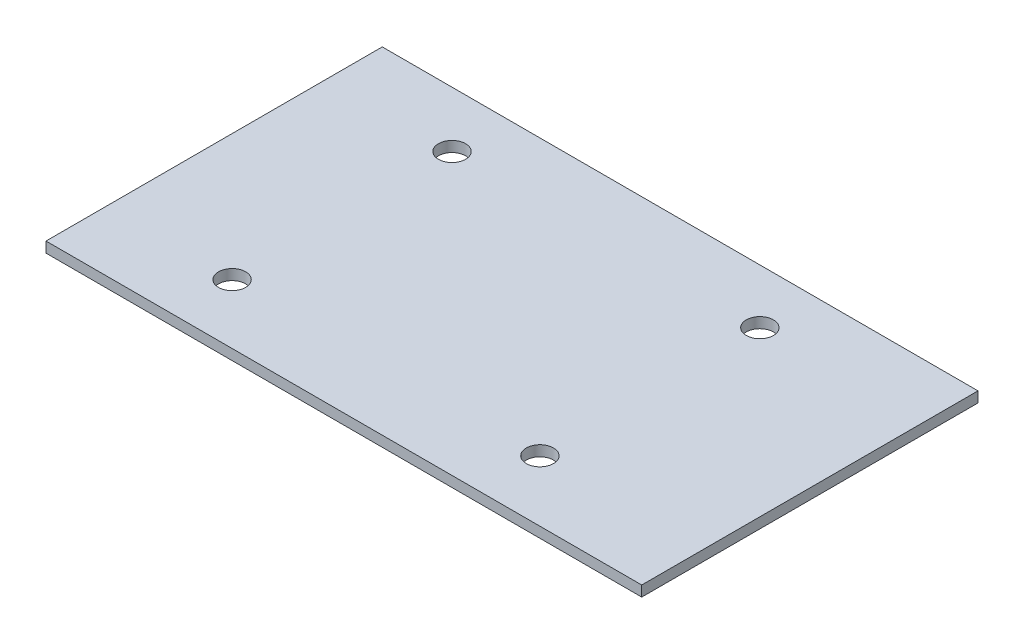
SolidWorks part; units mm, degrees
material "Cast Alloy Steel"
ref_plane "Front Plane" through (0, 0, 0) normal (0, 0, 1) x (1, 0, 0)
ref_plane "Top Plane" through (0, 0, 0) normal (0, 1, 0) x (1, 0, 0)
ref_plane "Right Plane" through (0, 0, 0) normal (1, 0, 0) x (0, 0, -1)
sketch "Sketch1" plane through (0, 0, 0) normal (0, 1, 0) x (1, 0, 0)
  line L1 (90, 50.8) -> (-90, 50.8)
  line L2 (90, 50.8) -> (90, -50.8)
  line L3 (90, -50.8) -> (-90, -50.8)
  line L4 (-90, 50.8) -> (-90, -50.8)
  line L5 (90, 50.8) -> (-90, -50.8) construction
  line L6 (90, -50.8) -> (-90, 50.8) construction
  circle A0 centre (-52.0866, 33.9689) radius 4.1
  circle A1 centre (40.5125, 34.3735) radius 4.1
  circle A2 centre (40.8041, -32.3729) radius 4.1
  circle A3 centre (-51.795, -32.7775) radius 4.1
  point P0 (0, 0)
  point P11 (-52.0875, 33.3735)
  point P18 (-51.795, -32.7775)
  point P19 (40.5125, 34.3735)
  point P20 (40.8041, -32.3729)
  point P21 (-52.0866, 33.9689)
  point P27 (0, 0)
  dimension "D3" = 8.2
  dimension "D1" = 101.6
  dimension "D2" = 180
extrude "Boss-Extrude1" add sketch "Sketch1" along normal blind 3.175
